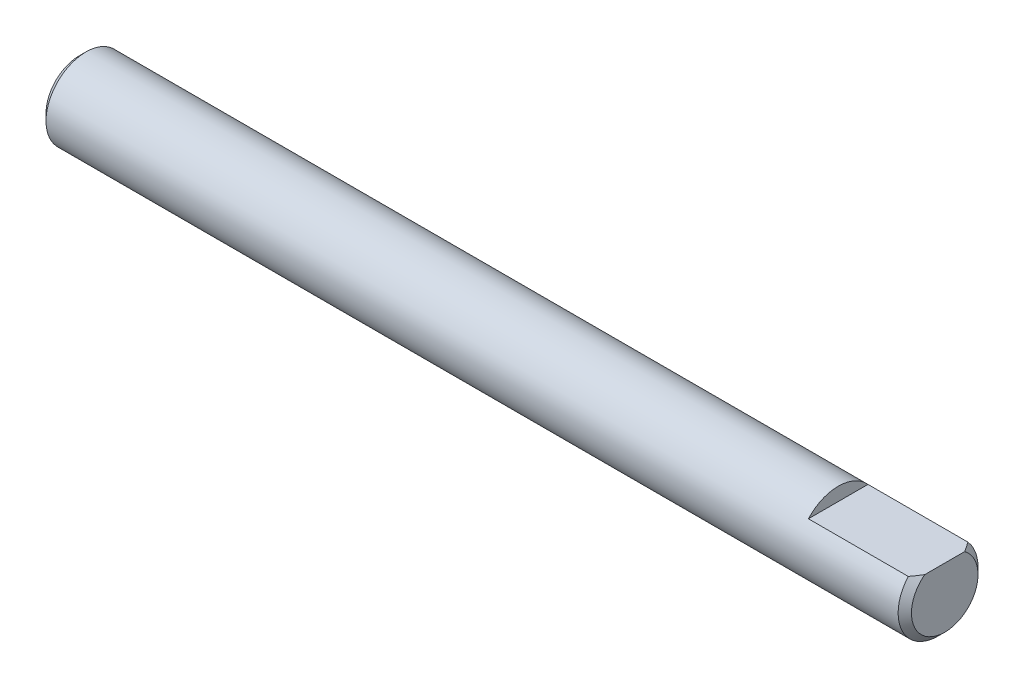
SolidWorks part; units mm, degrees
ref_plane "Front Plane" through (0, 0, 0) normal (0, 0, 1) x (1, 0, 0)
ref_plane "Top Plane" through (0, 0, 0) normal (0, 1, 0) x (1, 0, 0)
ref_plane "Right Plane" through (0, 0, 0) normal (1, 0, 0) x (0, 0, -1)
sketch "Sketch1" plane through (0, 0, 0) normal (1, 0, 0) x (0, 0, -1)
  circle A0 centre (0, 0) radius 3
  dimension "D1" = 6
extrude "Boss-Extrude1" add sketch "Sketch1" along normal mid plane 65
sketch "Sketch2" plane through (32.5, 0, 0) normal (1, 0, 0) x (0, 0, -1)
  line L0 (-2.2361, 2) -> (2.2361, 2)
  arc A0 (2.2361, 2) -> (-2.2361, 2) centre (0, 0) ccw
  dimension "D1" = 6
extrude "Cut-Extrude1" cut sketch "Sketch2" against normal blind 8
chamfer "Chamfer1" distance 0.5 angle 45 2 edges at (-32.5, 0, -3) (32.5, -3, 0)
